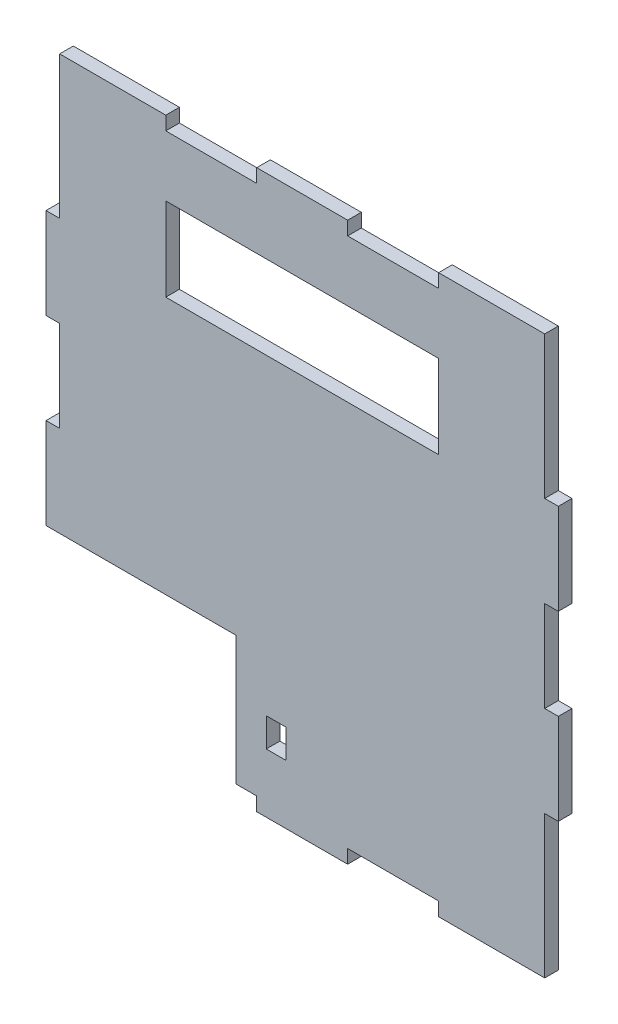
SolidWorks part; units mm, degrees
ref_plane "Front Plane" through (0, 0, 0) normal (0, 0, 1) x (1, 0, 0)
ref_plane "Top Plane" through (0, 0, 0) normal (0, 1, 0) x (1, 0, 0)
ref_plane "Right Plane" through (0, 0, 0) normal (1, 0, 0) x (0, 0, -1)
sketch "Sketch1" plane through (0, 0, 0) normal (0, 0, 1) x (1, 0, 0)
  line L8 (139.0327, 364.5) -> (139.0327, -6.5062) construction
  line L9 (109.0327, 5.5) -> (109.0327, -3.5)
  line L10 (169.0327, 5.5) -> (169.0327, -3.5)
  line L11 (49.0327, 5.5) -> (49.0327, -3.5)
  line L12 (229.0327, 5.5) -> (229.0327, -3.5)
  line L14 (229.0327, 355.5) -> (229.0327, 364.5)
  line L15 (169.0327, 355.5) -> (169.0327, 364.5)
  line L16 (49.0327, 355.5) -> (49.0327, 364.5)
  line L17 (109.0327, 355.5) -> (109.0327, 364.5)
  line L18 (-29.9673, 270.5) -> (-20.9673, 270.5)
  line L19 (299.0327, 210.5) -> (299.0327, 150.5)
  line L20 (-20.9673, 210.5) -> (-29.9673, 210.5)
  line L21 (-20.9673, 150.5) -> (-29.9673, 150.5)
  line L22 (-29.9673, 90.5) -> (-20.9673, 90.5)
  line L23 (308.0327, 90.5) -> (299.0327, 90.5)
  line L24 (299.0327, 150.5) -> (308.0327, 150.5)
  line L25 (299.0327, 210.5) -> (308.0327, 210.5)
  line L26 (308.0327, 270.5) -> (308.0327, 210.5)
  line L27 (308.0327, 270.5) -> (299.0327, 270.5)
  line L30 (-20.9673, 364.5) -> (49.0327, 364.5)
  line L32 (-29.9673, 150.5) -> (-29.9673, 90.5)
  line L33 (-20.9673, 5.8578) -> (-20.9673, -3.5)
  line L37 (229.0327, 364.5) -> (299.0327, 364.5)
  line L39 (169.0327, 355.5) -> (229.0327, 355.5)
  line L42 (308.0327, 150.5) -> (308.0327, 90.5)
  line L44 (229.0327, -3.5) -> (299.0327, -3.5)
  line L48 (169.0327, 5.5) -> (229.0327, 5.5)
  line L52 (-20.9673, 90.5) -> (-20.9673, 5.8578)
  line L54 (299.0327, 90.5) -> (299.0327, 5.5)
  line L60 (-20.9673, -3.5) -> (49.0327, -3.5)
  line L63 (49.0327, 355.5) -> (109.0327, 355.5)
  line L64 (-20.9673, 364.5) -> (-20.9673, 270.5)
  line L65 (49.0327, 5.5) -> (109.0327, 5.5)
  line L66 (299.0327, 364.5) -> (299.0327, 270.5)
  line L68 (299.0327, 5.5) -> (299.0327, -3.5)
  line L70 (109.0327, -3.5) -> (169.0327, -3.5)
  line L71 (109.0327, 364.5) -> (169.0327, 364.5)
  line L72 (-20.9673, 210.5) -> (-20.9673, 150.5)
  line L73 (-29.9673, 270.5) -> (-29.9673, 210.5)
  dimension "D2" = 320
  dimension "D4" = 60
  dimension "D6" = 60
  dimension "D8" = 9
  dimension "D9" = 9
  dimension "D3" = 350
extrude "Boss-Extrude1" add sketch "Sketch1" along normal blind 9
sketch "Sketch2" plane through (0, 0, 0) normal (0, 0, -1) x (-1, 0, 0)
  line L0 (9.3175, 44.75) -> (-116.6107, 44.75) construction
  line L1 (-49.0327, 5.5) -> (-109.0327, 5.5) construction
  line L2 (29.9673, 150.5) -> (29.9673, 90.5) construction
  line L3 (20.9673, 90.5) -> (-95.3292, 90.5)
  line L5 (9.3175, 5.5) -> (-95.3292, 5.5)
  line L6 (-95.3292, 90.5) -> (-95.3292, 5.5)
  line L7 (20.9673, 90.5) -> (29.9673, 90.5)
  line L9 (9.3175, 5.5) -> (29.9673, 5.5)
  line L10 (29.9673, 90.5) -> (29.9673, 5.5)
  line L11 (20.9673, 90.5) -> (20.9673, -3.5) construction
  line L12 (29.9673, 90.5) -> (20.9673, 90.5) construction
  line L13 (-51.7237, 5.5) -> (23.1634, 5.5)
  line L14 (-51.7237, 5.5) -> (-51.7237, -20.2043)
  line L15 (-51.7237, -20.2043) -> (23.1634, -20.2043)
  line L16 (23.1634, 5.5) -> (23.1634, -20.2043)
  dimension "D2" = 39.25
extrude "Cut-Extrude1" cut sketch "Sketch2" against normal blind 10
sketch "Sketch3" plane through (0, 0, 0) normal (0, 0, -1) x (-1, 0, 0)
  line L0 (-95.3292, 90.5) -> (-95.3292, 5.5) construction
  line L1 (-115.3292, 54.5) -> (-128.3292, 54.5)
  line L2 (-115.3292, 54.5) -> (-115.3292, 35.5)
  line L3 (-115.3292, 35.5) -> (-128.3292, 35.5)
  line L4 (-128.3292, 54.5) -> (-128.3292, 35.5)
  line L5 (-95.3292, 5.5) -> (-109.0327, 5.5) construction
  dimension "D1" = 13
  dimension "D2" = 19
  dimension "D3" = 20
  dimension "D4" = 30
extrude "Cut-Extrude2" cut sketch "Sketch3" against normal blind 10
sketch "Sketch4" plane through (0, 0, 0) normal (0, 0, -1) x (-1, 0, 0)
  line L0 (-142.1888, 315.4295) -> (-142.1888, 315.5) construction
  line L1 (-169.0327, 355.5) -> (-229.0327, 355.5) construction
  line L2 (-299.0327, 364.5) -> (-299.0327, 270.5) construction
  line L3 (-229.0327, 315.5) -> (-49.0327, 315.5)
  line L4 (-229.0327, 315.5) -> (-229.0327, 260.5)
  line L5 (-229.0327, 260.5) -> (-49.0327, 260.5)
  line L6 (-49.0327, 315.5) -> (-49.0327, 260.5)
  line L7 (20.9673, 364.5) -> (20.9673, 270.5) construction
  line L8 (-139.0327, 364.5) -> (-139.0327, 322.601) construction
  line L9 (-109.0327, 364.5) -> (-169.0327, 364.5) construction
  dimension "D1" = 90
  dimension "D2" = 90
  dimension "D3" = 55
  dimension "D4" = 40
  dimension "D5" = 320
extrude "Cut-Extrude3" cut sketch "Sketch4" against normal through all
